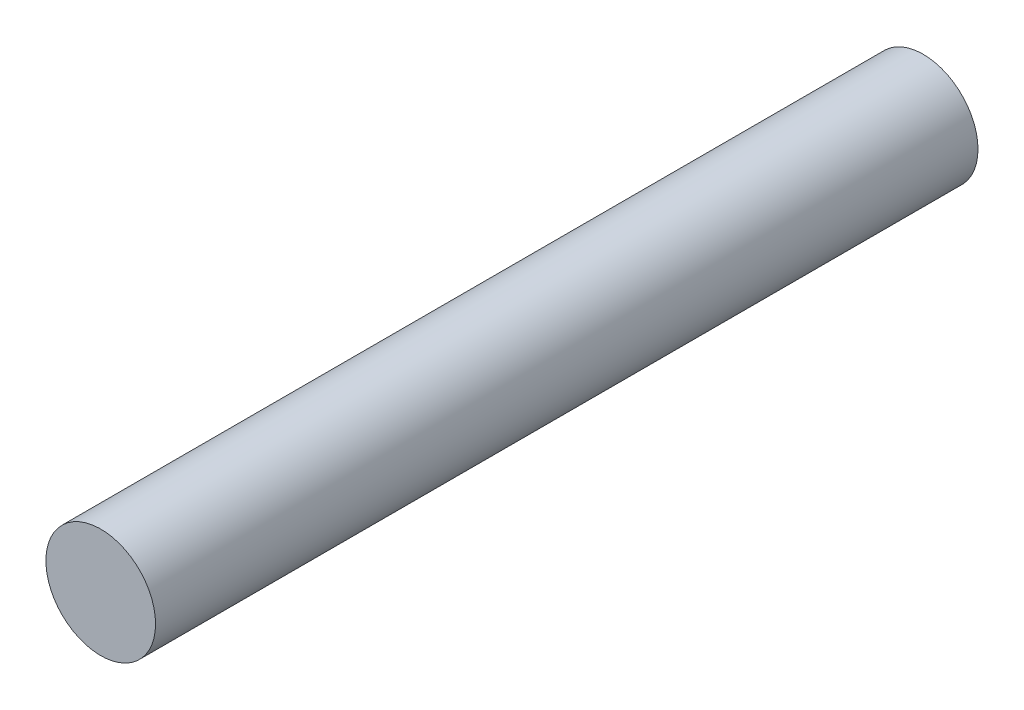
SolidWorks part; units mm, degrees
material "AISI 304"
ref_plane "前视基准面" through (0, 0, 0) normal (0, 0, 1) x (1, 0, 0)
ref_plane "上视基准面" through (0, 0, 0) normal (0, 1, 0) x (1, 0, 0)
ref_plane "右视基准面" through (0, 0, 0) normal (1, 0, 0) x (0, 0, -1)
sketch "草图1" plane through (0, 0, 0) normal (0, 0, 1) x (1, 0, 0)
  circle A0 centre (0, 0) radius 5
  dimension "D1" = 10
extrude "凸台-拉伸1" add sketch "草图1" along normal blind 75
